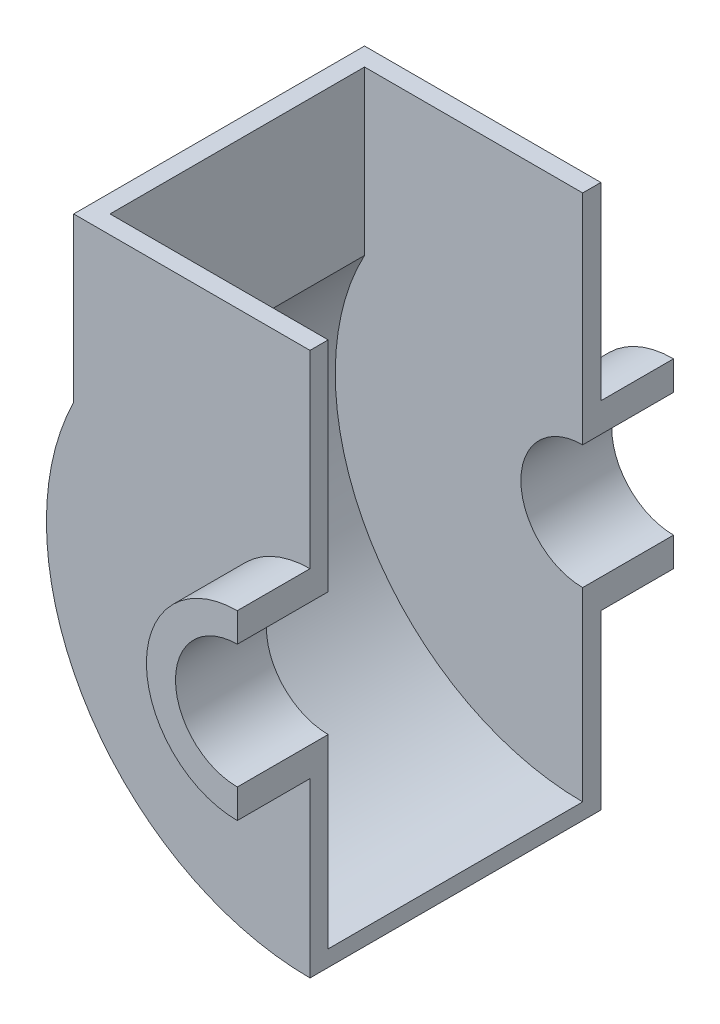
SolidWorks part; units mm, degrees
ref_plane "Front Plane" through (0, 0, 0) normal (0, 0, 1) x (1, 0, 0)
ref_plane "Top Plane" through (0, 0, 0) normal (0, 1, 0) x (1, 0, 0)
ref_plane "Right Plane" through (0, 0, 0) normal (1, 0, 0) x (0, 0, -1)
sketch "Sketch1" plane through (0, 0, 0) normal (0, 0, 1) x (1, 0, 0)
  line L0 (0, 25) -> (0, 17)
  line L1 (0, -17) -> (0, -25)
  arc A0 (0, 17) -> (0, -17) centre (0, 0) ccw
  arc A1 (0, 25) -> (0, -25) centre (0, 0) ccw
  dimension "D1" = 34
  dimension "D2" = 50
ref_plane "Plane1" through (0, 0, -40) normal (0, 0, 1) x (1, 0, 0)
extrude "Boss-Extrude1" add sketch "Sketch1" along normal blind 20 and the other way blind 5
sketch "Sketch5" plane through (0, 0, 0) normal (0, 0, 1) x (1, 0, 0)
  line L0 (0, -25) -> (0, -72.5)
  line L1 (0, 25) -> (0, 77)
  line L2 (0, 77) -> (-65, 77)
  line L3 (-65, 77) -> (-65, 32.1131)
  arc A0 (-65, 32.1131) -> (0, -72.5) centre (0, 0) ccw
  arc A1 (0, 25) -> (0, -25) centre (0, 0) ccw
  arc A2 (0, 25) -> (0, -25) centre (0, 0) ccw construction
  dimension "D1" = 145
  dimension "D2" = 52
  dimension "D3" = 65
extrude "Boss-Extrude2" add sketch "Sketch5" against normal blind 5 contours A1 L1 L2 L3 A0 L0
ref_plane "Plane2" through (0, 0, -40) normal (0, 0, 1) x (1, 0, 0)
mirror "Mirror3" about plane through (0, 0, -40) normal (0, 0, 1) of bodies 106
sketch "Sketch9" plane through (0, 0, -5) normal (0, 0, -1) x (-1, 0, 0)
  line L0 (65, 32.1131) -> (65, 77)
  line L1 (65, 77) -> (60, 77)
  line L2 (0, 77) -> (65, 77) construction
  line L3 (60, 77) -> (60, 32.1131)
  line L4 (0, -68.0533) -> (0, -72.5)
  arc A0 (0, -72.5) -> (65, 32.1131) centre (0, 0) ccw
  arc A1 (0, -68.0533) -> (60, 32.1131) centre (0, 0) ccw
  dimension "D1" = 5
extrude "Boss-Extrude3" add sketch "Sketch9" along normal up to surface (70 mm away)
